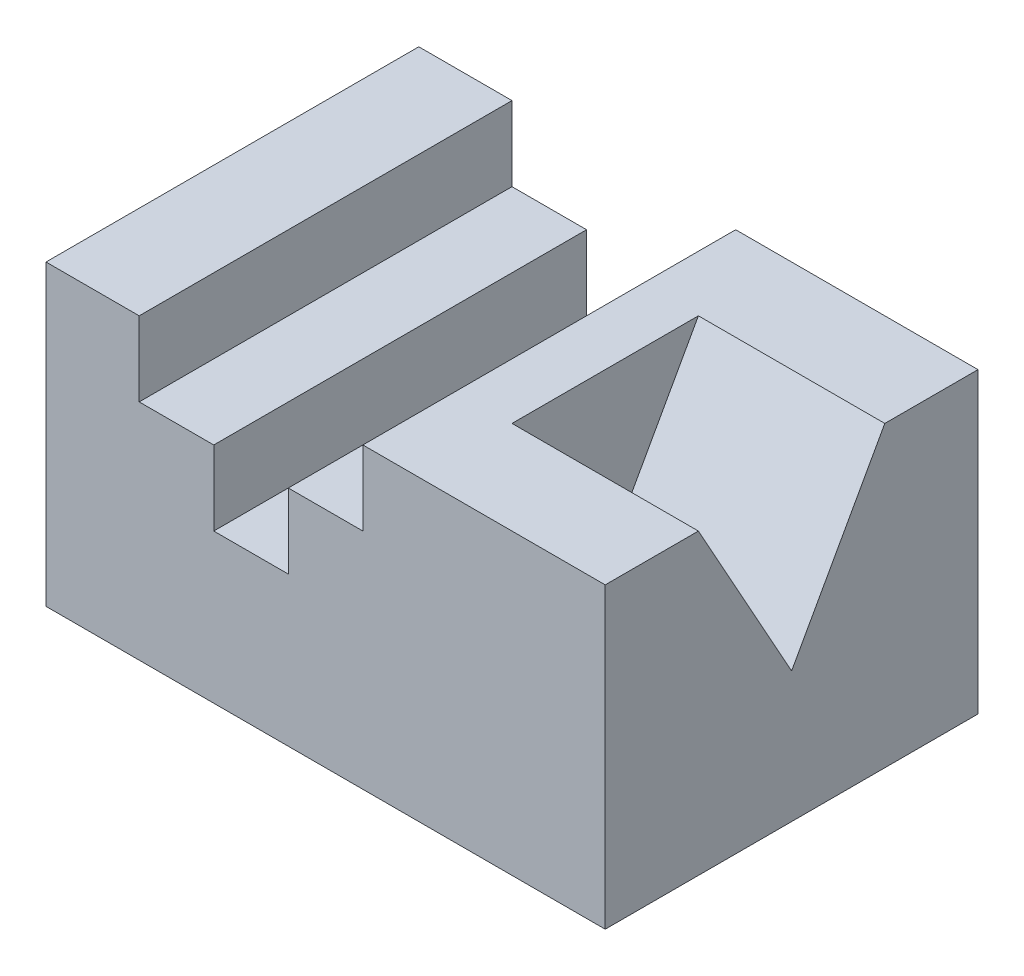
SolidWorks part; units mm, degrees
ref_plane "Front Plane" through (0, 0, 0) normal (0, 0, 1) x (1, 0, 0)
ref_plane "Top Plane" through (0, 0, 0) normal (0, 1, 0) x (1, 0, 0)
ref_plane "Right Plane" through (0, 0, 0) normal (1, 0, 0) x (0, 0, -1)
sketch "Sketch1" plane through (0, 0, 0) normal (0, 0, 1) x (1, 0, 0)
  line L0 (0, 80) -> (25, 80)
  line L1 (0, 0) -> (150, 0)
  line L2 (0, 0) -> (0, 80)
  line L3 (0, 80) -> (150, 80)
  line L4 (150, 0) -> (150, 80)
  line L5 (25, 80) -> (25, 60)
  line L6 (25, 60) -> (45, 60)
  line L7 (45, 60) -> (45, 40)
  line L8 (45, 40) -> (65, 40)
  line L9 (65, 40) -> (65, 60)
  line L10 (65, 60) -> (85, 60)
  line L11 (85, 60) -> (85, 80)
  line L12 (85, 80) -> (150, 80)
  dimension "D1" = 150
  dimension "D2" = 80
  dimension "D3" = 25
  dimension "D4" = 20
  dimension "D5" = 20
  dimension "D6" = 20
  dimension "D7" = 20
  dimension "D8" = 20
extrude "Boss-Extrude1" add sketch "Sketch1" against normal blind 100 contours L11 L10 L9 L8 L7 L6 L5 L0 L2 L1 L4 L3
sketch "Sketch2" plane through (150, 0, 0) normal (1, 0, 0) x (0, 0, -1)
  line L1 (100, 80) -> (0, 80) construction
  line L2 (25, 80) -> (50, 35)
  line L3 (50, 35) -> (75, 80)
  line L5 (0, 0) -> (0, 80) construction
  line L6 (25, 80) -> (75, 80)
  point P0 (0, 0)
  dimension "D1" = 25
  dimension "D2" = 50
  dimension "D3" = 45
  dimension "D4" = 25
extrude "Cut-Extrude1" cut sketch "Sketch2" against normal blind 50 contours L2 L3 L6
